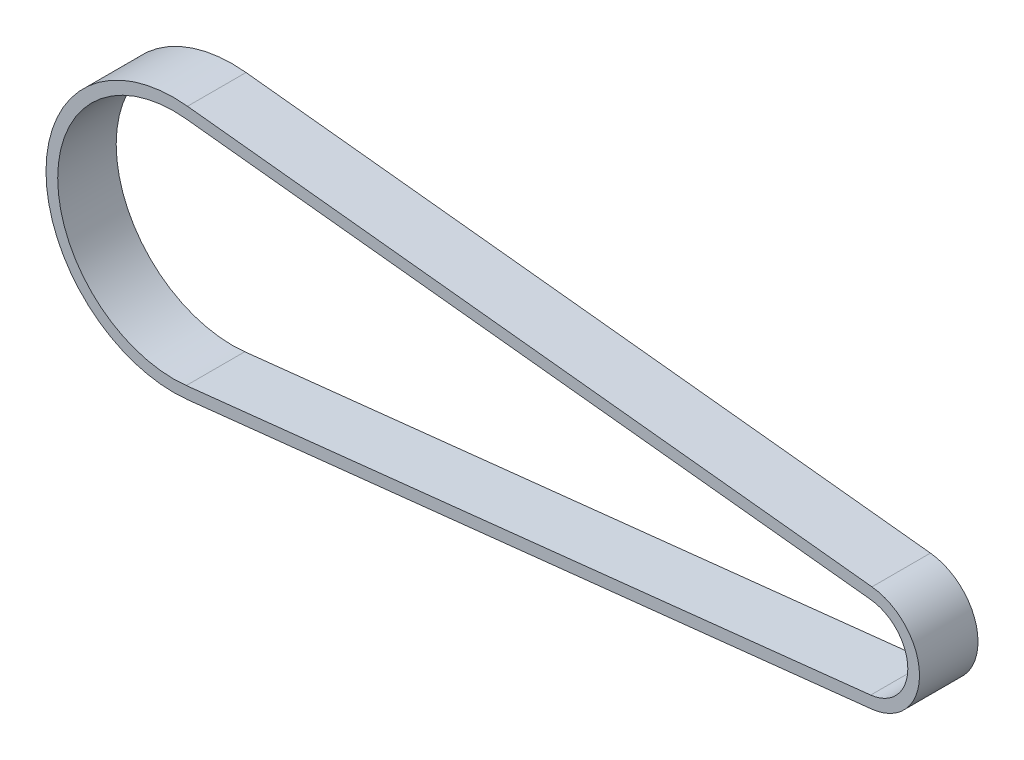
SolidWorks part; units mm, degrees
ref_plane "Front Plane" through (0, 0, 0) normal (0, 0, 1) x (1, 0, 0)
ref_plane "Top Plane" through (0, 0, 0) normal (0, 1, 0) x (1, 0, 0)
ref_plane "Right Plane" through (0, 0, 0) normal (1, 0, 0) x (0, 0, -1)
sketch "Sketch2" plane through (0, 0, 0) normal (0, 0, 1) x (1, 0, 0)
  line L0 (0, 0) -> (1, 0) construction
  line L1 (0, 0) -> (0, 1) construction
  line L2 (2.1325, 19.7301) -> (119.1457, 7.0829)
  line L3 (119.1474, -7.0546) -> (2.1372, -19.7296)
  arc A0 (2.1372, -19.7296) -> (2.1325, 19.7301) centre (0, 0) cw
  arc A1 (119.1457, 7.0829) -> (119.1474, -7.0546) centre (118.3817, 0.0141) cw
extrude "Extrude-Thin1" add sketch "Sketch2" along normal mid plane 10 thin thin type one direction wall 2
